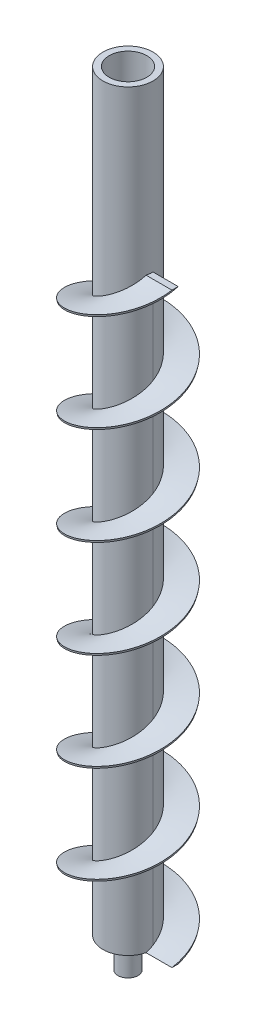
SolidWorks part; units mm, degrees
material "AISI 304"
ref_plane "前视基准面" through (0, 0, 0) normal (0, 0, 1) x (1, 0, 0)
ref_plane "上视基准面" through (0, 0, 0) normal (0, 1, 0) x (1, 0, 0)
ref_plane "右视基准面" through (0, 0, 0) normal (1, 0, 0) x (0, 0, -1)
sketch "Sketch1" plane through (0, 0, 0) normal (0, 1, 0) x (1, 0, 0)
  circle A0 centre (0, 0) radius 10
  dimension "D1" = 20
extrude "Extrude1" add sketch "Sketch1" along normal blind 300
sketch "Sketch2" plane through (0, 0, 0) normal (0, -1, 0) x (1, 0, 0)
  circle A0 centre (0, 0) radius 20
  dimension "D1" = 40
curve "Helix/Spiral1" pitch 39 height 234 turns 6
sketch "Sketch3" plane through (0, 0, 0) normal (0, -1, 0) x (-1, 0, 0)
  line L0 (0, 0) -> (-38.7359, 0) construction
  line L2 (0, 0) -> (-20, 0)
  line L3 (0, 0) -> (0, -2.4834)
  line L4 (0, -2.4834) -> (-20, -2.4834)
  line L5 (-20, 0) -> (-20, -2.4834)
sweep "Sweep1" add profiles "Sketch3" path "Helix/Spiral1"
sketch "Sketch4" plane through (0, 0, 0) normal (0, -1, 0) x (1, 0, 0)
  circle A0 centre (0, 0) radius 4
  dimension "D1" = 8
extrude "Extrude2" add sketch "Sketch4" along normal blind 12
sketch "Sketch5" plane through (0, 300, 0) normal (0, 1, 0) x (1, 0, 0)
  circle A0 centre (0, 0) radius 7.5
  dimension "D1" = 15
extrude "Extrude3" cut sketch "Sketch5" against normal blind 30
sketch "Sketch6" plane through (0, 0, 0) normal (0, 0, 1) x (1, 0, 0)
  line L0 (10, 300) -> (-10, 300) construction
  circle A0 centre (0, 288) radius 2.6
  dimension "D1" = 5.2
  dimension "D2" = 12
extrude "Extrude4" cut sketch "Sketch6" against normal blind 30
